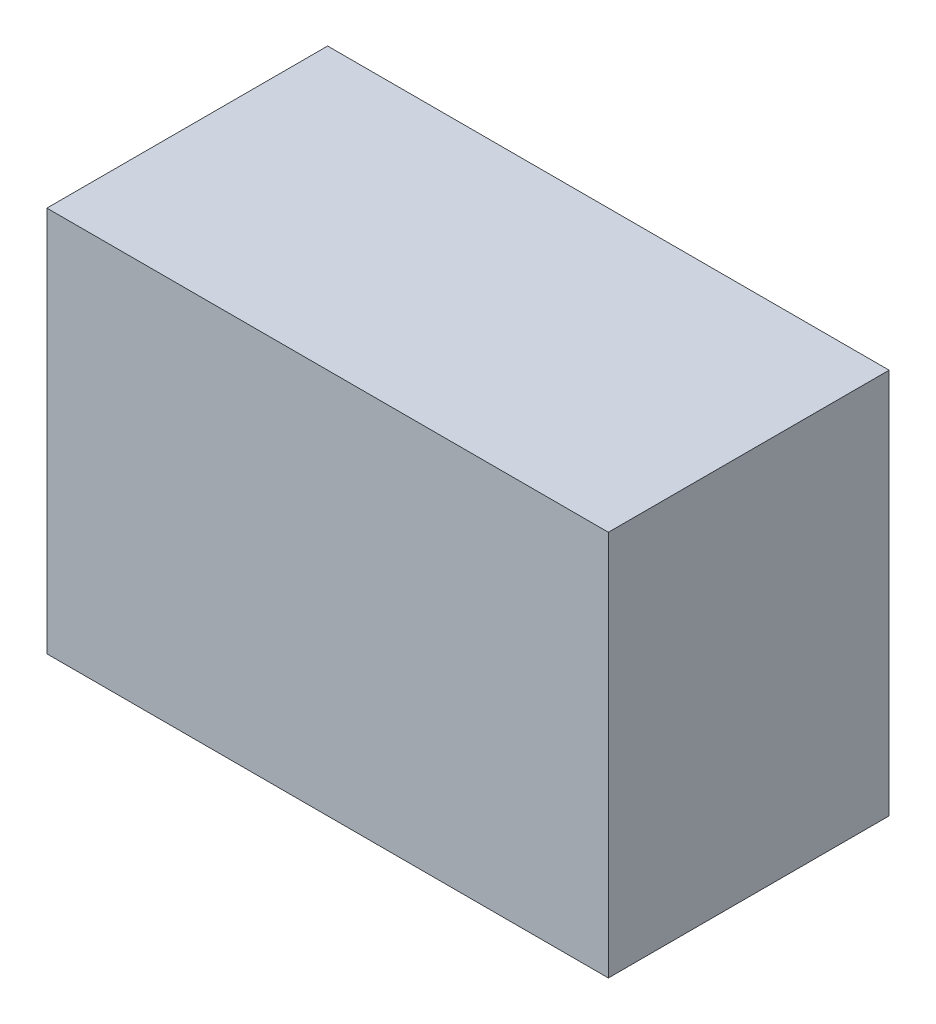
SolidWorks part; units mm, degrees
ref_plane "Front Plane" through (0, 0, 0) normal (0, 0, 1) x (1, 0, 0)
ref_plane "Top Plane" through (0, 0, 0) normal (0, 1, 0) x (1, 0, 0)
ref_plane "Right Plane" through (0, 0, 0) normal (1, 0, 0) x (0, 0, -1)
sketch "Sketch1" plane through (0, 0, 0) normal (0, 0, 1) x (1, 0, 0)
  line L1 (0, 0) -> (-16, 0)
  line L2 (0, 0) -> (0, 11)
  line L3 (0, 11) -> (-16, 11)
  line L4 (-16, 0) -> (-16, 11)
  dimension "D1" = 11
  dimension "D2" = 16
extrude "Boss-Extrude1" add sketch "Sketch1" along normal blind 8
